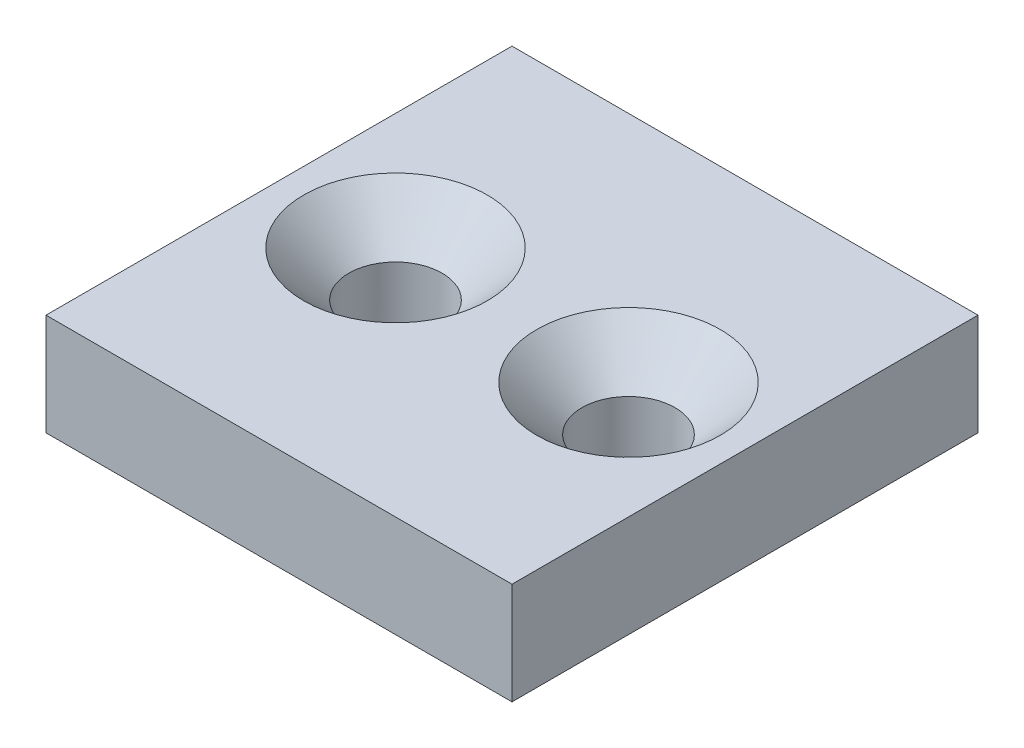
SolidWorks part; units mm, degrees
ref_plane "Front Plane" through (0, 0, 0) normal (0, 0, 1) x (1, 0, 0)
ref_plane "Top Plane" through (0, 0, 0) normal (0, 1, 0) x (1, 0, 0)
ref_plane "Right Plane" through (0, 0, 0) normal (1, 0, 0) x (0, 0, -1)
sketch "Sketch1" plane through (0, 0, 0) normal (0, 1, 0) x (1, 0, 0)
  line L1 (-16, -16) -> (16, -16)
  line L2 (-16, -16) -> (-16, 16)
  line L3 (-16, 16) -> (16, 16)
  line L4 (16, -16) -> (16, 16)
  line L5 (-16, -16) -> (16, 16) construction
  line L6 (-16, 16) -> (16, -16) construction
  point P0 (0, 0)
  dimension "D1" = 32
  dimension "D2" = 32
extrude "Boss-Extrude1" add sketch "Sketch1" along normal blind 7
hole_wizard "CSK for M6 Flat Head Machine Screw1" positions "Sketch3" profile "Sketch2" countersink size "M6" standard "ANSI Metric" end condition up to next
sketch "Sketch3" plane through (0, 7, 0) normal (0, 1, 0) x (1, 0, 0)
  line L0 (-16, 16) -> (-16, -16) construction
  point P0 (8, 0)
  point P3 (-8, 0)
  point P8 (0, 0)
  dimension "D1" = 8
  dimension "D2" = 16
sketch "Sketch2" plane through (8, 7, 0) normal (1, 0, 0) x (0, 0, 1)
  line L0 (0, 0) -> (0, 7)
  line L1 (0, 7) -> (3.2, 7)
  line L2 (3.2, 7) -> (3.2, 3.1)
  line L3 (3.2, 3.1) -> (6.3, 0)
  line L5 (6.3, 0) -> (0, 0)
  line L6 (-3.2, 3.1) -> (-6.3, 0) construction
  line L11 (0, -6.35) -> (0, 107.95) construction
  dimension "Thru Hole Dia." = 6.4
  dimension "Thru Hole Depth" = 7
  dimension "Near C'Sink Dia." = 12.6
  dimension "Near C'Sink Angle" = 90
